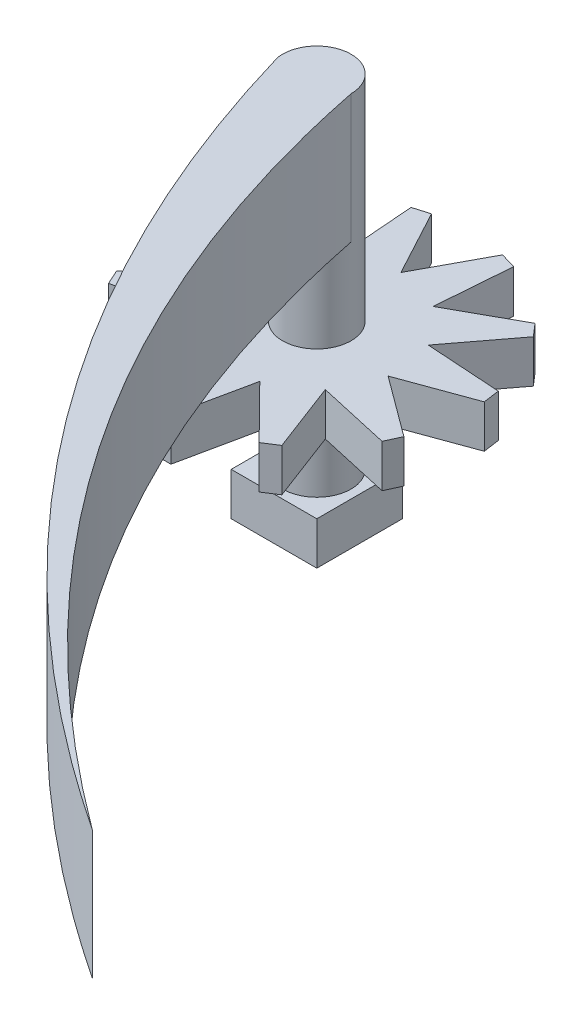
SolidWorks part; units mm, degrees
ref_plane "Plan de face" through (0, 0, 0) normal (0, 0, 1) x (1, 0, 0)
ref_plane "Plan de dessus" through (0, 0, 0) normal (0, 1, 0) x (1, 0, 0)
ref_plane "Plan de droite" through (0, 0, 0) normal (1, 0, 0) x (0, 0, -1)
sketch "Esquisse1" plane through (0, 0, 0) normal (0, 1, 0) x (1, 0, 0)
  circle A0 centre (0, 0) radius 2
extrude "Boss.-Extru.1" add sketch "Esquisse1" along normal blind 5
sketch "Esquisse2" plane through (0, 5, 0) normal (0, 1, 0) x (1, 0, 0)
  line L0 (0, -37.8316) -> (0, 19.5955) construction
  arc A1 (2, 0) -> (-1.9752, -0.3137) centre (0, 0) ccw
  spline S2 degree 2 poles (-1.9752, -0.3137) (6.018, -27.7557) (31.6707, -44.7855) knots 0 0 0 1 1 1
  spline S3 degree 2 poles (2, 0) (7.4311, -26.8848) (31.6707, -44.7855) knots 0 0 0 1 1 1
  point P6 (0, 19.5955)
extrude "Boss.-Extru.2" add sketch "Esquisse2" along normal blind 7.5
sketch "Esquisse4" plane through (0, 0, 0) normal (0, -1, 0) x (1, 0, 0)
  line L0 (-0.4807, 9.001) -> (0.4807, 9.001)
  line L1 (-0.4807, 9.001) -> (-1.3842, 4.7142)
  line L2 (0.4807, 9.001) -> (1.3842, 4.7142)
  line L3 (4.4619, 7.8321) -> (1.3842, 4.7142)
  line L4 (5.2707, 7.3123) -> (3.7131, 3.2174)
  line L5 (4.4619, 7.8321) -> (5.2707, 7.3123)
  line L6 (7.9879, 4.1765) -> (3.7131, 3.2174)
  line L7 (8.3873, 3.3019) -> (4.8632, 0.6992)
  line L8 (7.9879, 4.1765) -> (8.3873, 3.3019)
  line L9 (8.9778, -0.8052) -> (4.8632, 0.6992)
  line L10 (8.841, -1.7568) -> (4.4692, -2.041)
  line L11 (8.9778, -0.8052) -> (8.841, -1.7568)
  line L12 (7.1173, -5.5311) -> (4.4692, -2.041)
  line L13 (6.4877, -6.2577) -> (2.6563, -4.1332)
  line L14 (7.1173, -5.5311) -> (6.4877, -6.2577)
  line L15 (2.9971, -8.501) -> (2.6563, -4.1332)
  line L16 (2.0746, -8.7719) -> (0, -4.9132)
  line L17 (2.9971, -8.501) -> (2.0746, -8.7719)
  line L18 (-2.0746, -8.7719) -> (0, -4.9132)
  line L19 (-2.9971, -8.501) -> (-2.6563, -4.1332)
  line L20 (-2.0746, -8.7719) -> (-2.9971, -8.501)
  line L21 (-6.4877, -6.2577) -> (-2.6563, -4.1332)
  line L22 (-7.1173, -5.5311) -> (-4.4692, -2.041)
  line L23 (-6.4877, -6.2577) -> (-7.1173, -5.5311)
  line L24 (-8.841, -1.7568) -> (-4.4692, -2.041)
  line L25 (-8.9778, -0.8052) -> (-4.8632, 0.6992)
  line L26 (-8.841, -1.7568) -> (-8.9778, -0.8052)
  line L27 (-8.3873, 3.3019) -> (-4.8632, 0.6992)
  line L28 (-7.9879, 4.1765) -> (-3.7131, 3.2174)
  line L29 (-8.3873, 3.3019) -> (-7.9879, 4.1765)
  line L30 (-5.2707, 7.3123) -> (-3.7131, 3.2174)
  line L31 (-4.4619, 7.8321) -> (-1.3842, 4.7142)
  line L32 (-5.2707, 7.3123) -> (-4.4619, 7.8321)
  point P1 (0, 0)
  point P4 (0, 9.001)
  point P7 (0, 0)
  point P37 (0, 0)
extrude "Boss.-Extru.3" add sketch "Esquisse4" along normal blind 2.5
sketch "Esquisse5" plane through (0, -2.5, 0) normal (0, -1, 0) x (1, 0, 0)
  circle A0 centre (0, 0) radius 2
extrude "Boss.-Extru.4" add sketch "Esquisse5" along normal blind 5
sketch "Esquisse6" plane through (0, -7.5, 0) normal (0, -1, 0) x (1, 0, 0)
  line L1 (-2.5, -2.5) -> (2.5, -2.5)
  line L2 (-2.5, -2.5) -> (-2.5, 2.5)
  line L3 (-2.5, 2.5) -> (2.5, 2.5)
  line L4 (2.5, -2.5) -> (2.5, 2.5)
  line L5 (-2.5, -2.5) -> (2.5, 2.5) construction
  line L6 (-2.5, 2.5) -> (2.5, -2.5) construction
  point P0 (0, 0)
extrude "Boss.-Extru.5" add sketch "Esquisse6" along normal blind 2.5
